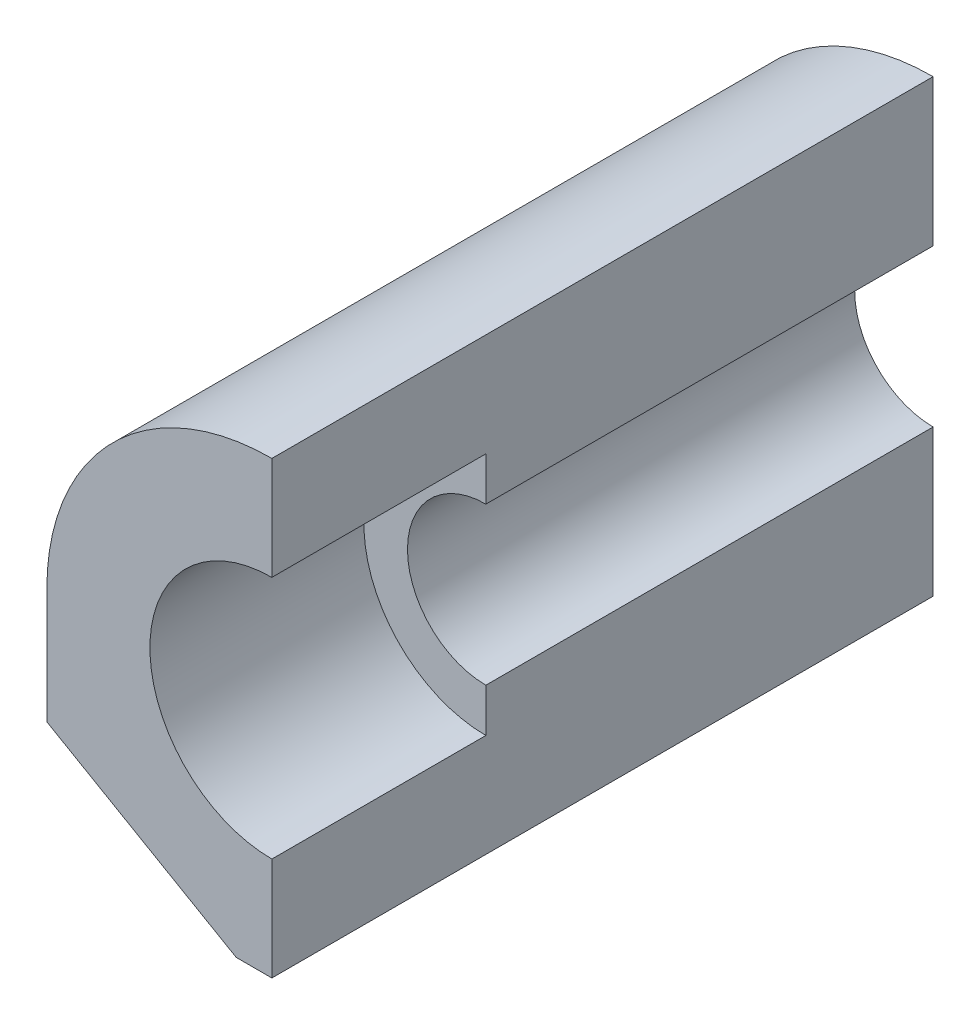
SolidWorks part; units mm, degrees
ref_plane "Front Plane" through (0, 0, 0) normal (0, 0, 1) x (1, 0, 0)
ref_plane "Top Plane" through (0, 0, 0) normal (0, 1, 0) x (1, 0, 0)
ref_plane "Right Plane" through (0, 0, 0) normal (1, 0, 0) x (0, 0, -1)
sketch "Sketch2" plane through (0, 0, 0) normal (0, 0, 1) x (1, 0, 0)
  line L0 (0, 0) -> (0, 87075.3523) construction
  line L1 (0, 0) -> (87075.3523, 0) construction
  line L2 (0, -28.575) -> (0, -82)
  line L3 (0, -82) -> (-13, -82)
  line L4 (-13, -82) -> (-82, -42.1628)
  line L5 (-82, -42.1628) -> (-82, 0)
  line L6 (0, 82) -> (0, 28.575)
  line L7 (-13, -82) -> (-103.8778, -82) construction
  arc A0 (0, 28.575) -> (0, -28.575) centre (0, 0) ccw
  arc A1 (-82, 0) -> (0, 82) centre (0, 0) cw
  dimension "D4" = 82
  dimension "D5" = 28.575
  dimension "D1" = 82
  dimension "D2" = 82
  dimension "D3" = 13
  dimension "D6" = 30
extrude "Boss-Extrude1" add sketch "Sketch2" against normal blind 241
sketch "Sketch3" plane through (0, 0, 0) normal (0, 0, 1) x (1, 0, 0)
  line L0 (0, 0) -> (0, 50000) construction
  line L1 (0, 0) -> (50000, 0) construction
  line L2 (0, 44.45) -> (0, 28.575)
  line L3 (0, -28.575) -> (0, -44.45)
  arc A0 (0, 44.45) -> (0, -44.45) centre (0, 0) ccw
  arc A1 (0, 28.575) -> (0, -28.575) centre (0, 0) ccw construction
  arc A2 (0, 28.575) -> (0, -28.575) centre (0, 0) ccw
  dimension "D1" = 44.45
extrude "Cut-Extrude1" cut sketch "Sketch3" against normal blind 78 contours A0 L3 A2 L2
sketch "Sketch4" plane through (0, 0, 0) normal (0, 0, 1) x (1, 0, 0)
  line L0 (-18.8518, 79.8036) -> (-11.1123, 76.751)
  line L1 (-11.1123, 76.751) -> (-41.1988, 0.4699)
  line L2 (-41.1988, 0.4699) -> (-80.4348, 15.9452)
  line L3 (0, 0) -> (0, 50000) construction
  line L4 (0, 0) -> (50000, 0) construction
  arc A0 (0, 82) -> (-82, 0) centre (0, 0) ccw construction
  point P12 (-18.8518, 79.8036)
  dimension "D1" = 82
equation "\"A\"= 241.00"
equation "\"B\"= 114.00"
equation "\"C\"= 82.00"
equation "\"D1@Sketch2\"=\"C\""
equation "\"D2@Sketch2\"=\"C\""
equation "\"D4@Sketch2\"=\"C\""
equation "\"D1@Boss-Extrude1\"=\"A\""
